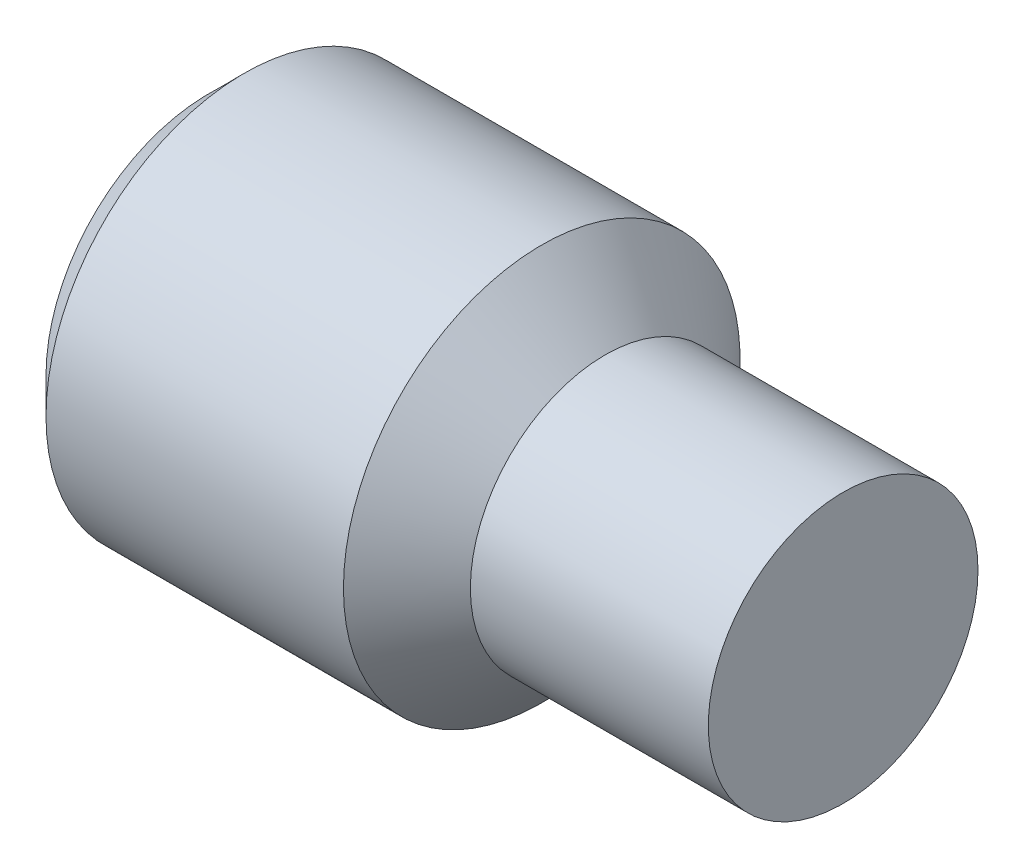
SolidWorks part; units mm, degrees
ref_plane "Спереди" through (0, 0, 0) normal (0, 0, 1) x (1, 0, 0)
ref_plane "Сверху" through (0, 0, 0) normal (0, 1, 0) x (1, 0, 0)
ref_plane "Справа" through (0, 0, 0) normal (1, 0, 0) x (0, 0, -1)
sketch "Эскиз1" plane through (0, 0, 0) normal (1, 0, 0) x (0, 0, -1)
  circle A0 centre (0, 0) radius 5
  dimension "D1" = 10
extrude "Вытянуть1" add sketch "Эскиз1" along normal blind 16
sketch "Эскиз2" plane through (0, 0, 0) normal (-1, 0, 0) x (0, 0, 1)
  line L0 (0, 2.8868) -> (-2.5, 1.4434)
  line L1 (-2.5, 1.4434) -> (-2.5, -1.4434)
  line L2 (-2.5, -1.4434) -> (0, -2.8868)
  line L3 (0, -2.8868) -> (2.5, -1.4434)
  line L4 (2.5, -1.4434) -> (2.5, 1.4434)
  line L5 (2.5, 1.4434) -> (0, 2.8868)
  line L6 (0, -2.8868) -> (0, 2.8868) construction
  circle A0 centre (0, 0) radius 2.8868
  dimension "D1" = 120
  dimension "D2" = 120
  dimension "D3" = 5
extrude "Вырез-Вытянуть1" cut sketch "Эскиз2" against normal blind 6 contours L2 L6 L0 L1 | L6 L3 L4 L5
sketch "Эскиз3" plane through (16, 0, 0) normal (1, 0, 0) x (0, 0, -1)
  circle A0 centre (0, 0) radius 5
  circle A1 centre (0, 0) radius 3.4
  circle A2 centre (0, 0) radius 5 construction
  dimension "D1" = 6.8
extrude "Вырез-Вытянуть2" cut sketch "Эскиз3" against normal blind 6
sketch "Эскиз4" plane through (0, 0, 0) normal (0, 0, 1) x (1, 0, 0)
  line L0 (0, 0) -> (16, 0) construction
  line L1 (16, -3.4) -> (16, 3.4) construction
  line L2 (10, 5) -> (10, 3.4)
  line L3 (10, 3.4) -> (8.4, 5)
  line L4 (8.4, 5) -> (10, 5)
  line L5 (10, 5) -> (13.8844, 5.9345)
  dimension "D1" = 45
revolve "Вырез-Повернуть1" cut sketch "Эскиз4" angle 360 about L0
sketch "Эскиз5" plane through (0, 0, 0) normal (0, 0, 1) x (1, 0, 0)
  line L0 (0, 0) -> (8.4, 0) construction
  line L1 (8.4, 5) -> (8.4, -5) construction
  line L2 (0, 5) -> (0, 4.1)
  line L3 (0, 5) -> (0, -5) construction
  line L4 (0, 4.1) -> (0.9, 5)
  line L5 (0.9, 5) -> (0, 5)
  dimension "D1" = 45
  dimension "D2" = 4.1
revolve "Вырез-Повернуть2" cut sketch "Эскиз5" angle 360 about L0
